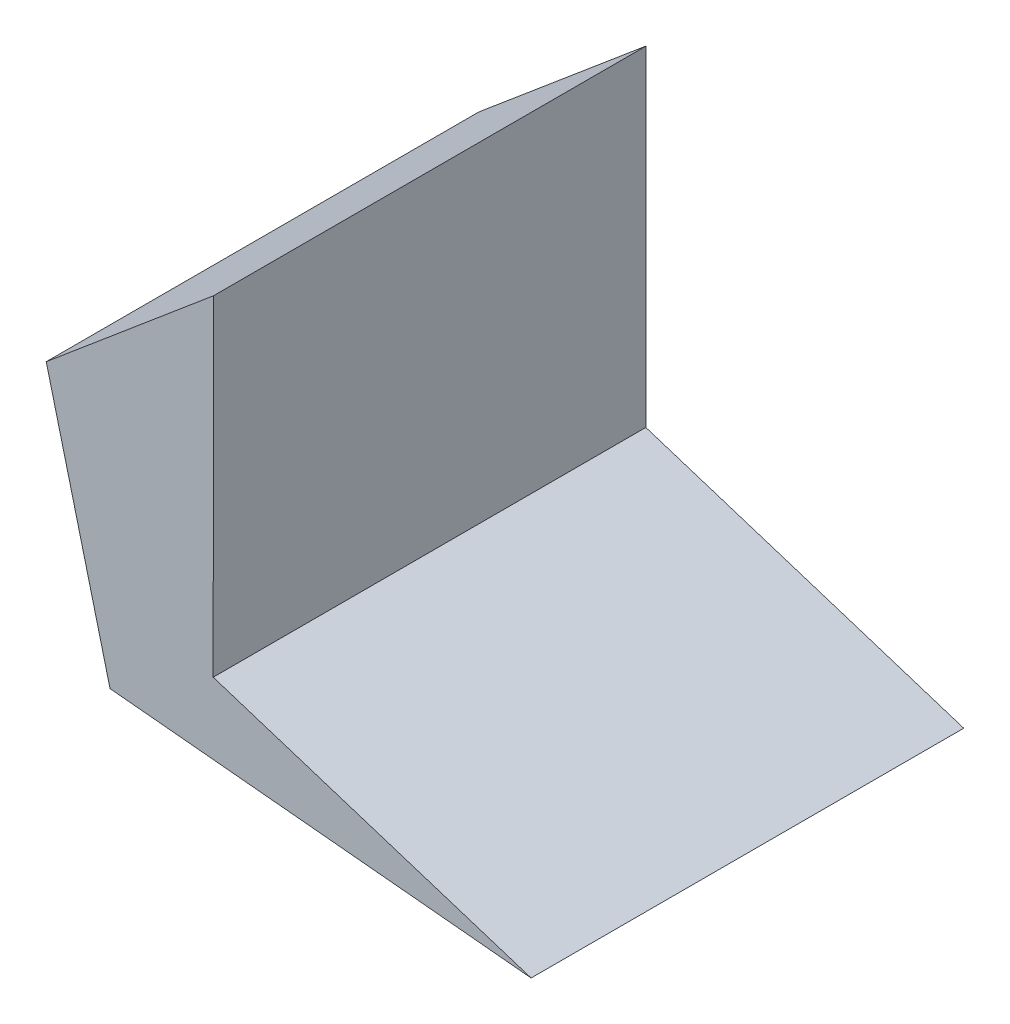
SolidWorks part; units mm, degrees
ref_plane "Front Plane" through (0, 0, 0) normal (0, 0, 1) x (1, 0, 0)
ref_plane "Top Plane" through (0, 0, 0) normal (0, 1, 0) x (1, 0, 0)
ref_plane "Right Plane" through (0, 0, 0) normal (1, 0, 0) x (0, 0, -1)
sketch "Sketch1" plane through (0, 0, 0) normal (0, 0, 1) x (1, 0, 0)
  line L0 (-158.1722, -49.7969) -> (-173.2578, -48.361)
  line L1 (-173.2578, -48.361) -> (-175.5432, -39.3609)
  line L2 (-175.5432, -39.3609) -> (-169.5526, -34.3208)
  line L3 (-169.5526, -34.3208) -> (-169.5623, -46.1603)
  line L4 (-169.5623, -46.1603) -> (-158.1722, -49.7969)
extrude "Boss-Extrude1" add sketch "Sketch1" along normal blind 15.5
